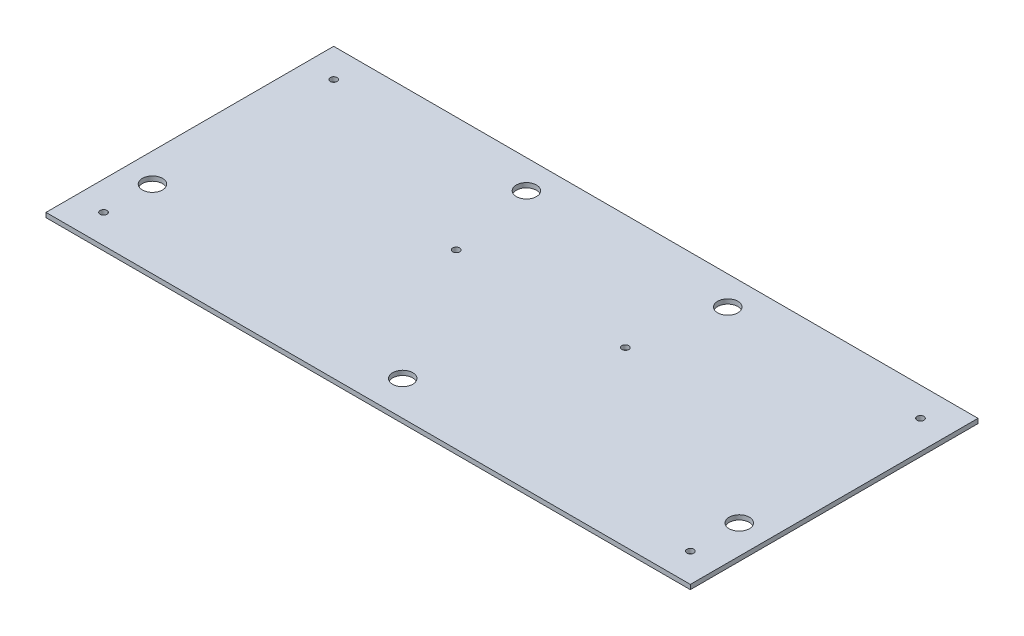
SolidWorks part; units mm, degrees
material "Epoxy, Unfilled"
ref_plane "Front Plane" through (0, 0, 0) normal (0, 0, 1) x (1, 0, 0)
ref_plane "Top Plane" through (0, 0, 0) normal (0, 1, 0) x (1, 0, 0)
ref_plane "Right Plane" through (0, 0, 0) normal (1, 0, 0) x (0, 0, -1)
sketch "Sketch1" plane through (0, 0, 0) normal (0, 1, 0) x (1, 0, 0)
  line L1 (112, -50) -> (-112, -50)
  line L2 (112, -50) -> (112, 50)
  line L3 (112, 50) -> (-112, 50)
  line L4 (-112, -50) -> (-112, 50)
  line L5 (112, -50) -> (-112, 50) construction
  line L6 (112, 50) -> (-112, -50) construction
  point P0 (0, 0)
  dimension "D1" = 224
  dimension "D2" = 100
extrude "Boss-Extrude1" add sketch "Sketch1" along normal blind 1.6
sketch "Sketch4" plane through (0, 0, 0) normal (0, 1, 0) x (1, 0, 0)
  line L0 (-112, 50) -> (-112, -50) construction
  line L1 (112, 50) -> (-112, 50) construction
  point P0 (-102, 40)
  dimension "D1" = 10
  dimension "D2" = 10
hole_wizard "M2 Clearance Hole1" positions "Sketch4" profile "Sketch3" hole size "M2" standard "ANSI Metric" end condition through all
sketch "Sketch3" plane through (-102, 0, -40) normal (1, 0, 0) x (0, 0, -1)
  line L0 (0, 0) -> (0, 1.6)
  line L1 (0, 1.6) -> (1.2, 1.6)
  line L2 (1.2, 1.6) -> (1.2, 0)
  line L5 (1.2, 0) -> (0, 0)
  line L11 (0, -6.35) -> (0, 107.95) construction
  dimension "Thru Hole Dia." = 2.4
  dimension "Thru Hole Depth" = 1.6
mirror "Mirror1" about plane through (0, 0, 0) normal (1, 0, 0) of "M2 Clearance Hole1"
mirror "Mirror2" about plane through (0, 0, 0) normal (0, 0, 1) of "Mirror1", "M2 Clearance Hole1"
sketch "Sketch5" plane through (0, 0, 0) normal (0, 1, 0) x (1, 0, 0)
  circle A0 centre (-35, 40) radius 3.5
  circle A1 centre (35, 40) radius 3.5
  circle A2 centre (0, -38) radius 3.5
  dimension "D1" = 7
extrude "Cut-Extrude2" cut sketch "Sketch5" along normal through all
sketch "Arduino_promicro" plane through (0, 0, 0) normal (0, 1, 0) x (1, 0, 0)
  line L0 (0, -0.88) -> (0, 0.88) construction
  line L1 (-9, 25) -> (9, 25)
  line L2 (-9, 25) -> (-9, -11.9)
  line L3 (-9, -11.9) -> (9, -11.9)
  line L4 (9, 25) -> (9, -11.9)
  line L5 (112, 50) -> (-112, 50) construction
  dimension "D1" = 18
  dimension "D2" = 36.9
  dimension "D3" = 9
  dimension "D4" = 25
sketch "Sketch10" plane through (0, 0, 0) normal (0, 1, 0) x (1, 0, 0)
  point P0 (-102, -23)
  point P3 (-29.413, 10)
  point P6 (29.413, 10)
  point P10 (102, -23)
hole_wizard "M2 Clearance Hole2" positions "Sketch10" profile "Sketch9" hole size "M2" standard "ANSI Metric" end condition through all
sketch "Sketch9" plane through (-102, 0, 23) normal (1, 0, 0) x (0, 0, -1)
  line L0 (0, 0) -> (0, 1.6)
  line L1 (0, 1.6) -> (1.2, 1.6)
  line L2 (1.2, 1.6) -> (1.2, 0)
  line L5 (1.2, 0) -> (0, 0)
  line L11 (0, -6.35) -> (0, 107.95) construction
  dimension "Thru Hole Dia." = 2.4
  dimension "Thru Hole Depth" = 1.6
sketch "Sketch12" plane through (0, 0, 0) normal (0, 1, 0) x (1, 0, 0)
  circle A0 centre (-102, -23) radius 3.5
  circle A1 centre (102, -23) radius 3.5
extrude "Cut-Extrude3" cut sketch "Sketch12" along normal blind 2
